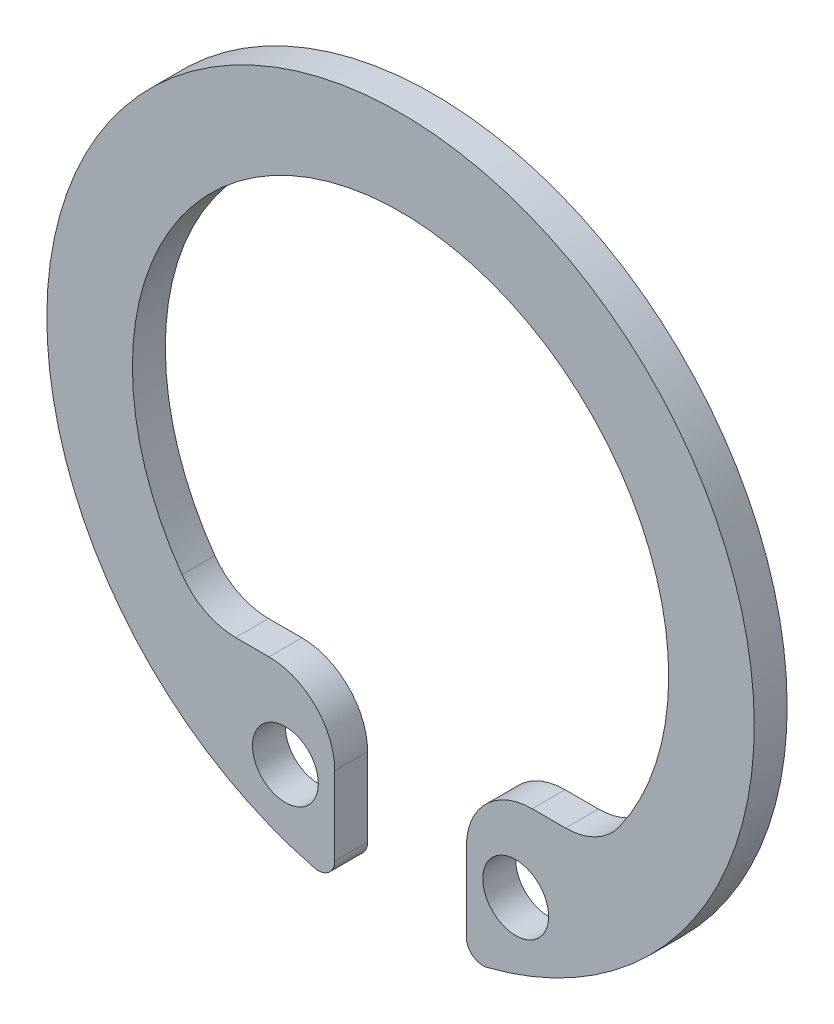
SolidWorks part; units mm, degrees
ref_plane "Ön Düzlem" through (0, 0, 0) normal (0, 0, 1) x (1, 0, 0)
ref_plane "Üst Düzlem" through (0, 0, 0) normal (0, 1, 0) x (1, 0, 0)
ref_plane "Sağ Düzlem" through (0, 0, 0) normal (1, 0, 0) x (0, 0, -1)
sketch "Çizim1" plane through (0, 0, 0) normal (0, 0, 1) x (1, 0, 0)
  line L0 (0, -8.15) -> (0, -10.75) construction
  line L1 (-2, -5.5623) -> (-2, -10.5623)
  line L2 (2, -5.5623) -> (2, -10.5623)
  line L3 (-2, -8.15) -> (-2, -10.75) construction
  line L4 (2, -8.15) -> (2, -10.75) construction
  line L5 (-2, -5.5623) -> (-5.9568, -5.5623)
  line L6 (2, -5.5623) -> (5.9568, -5.5623)
  arc A0 (2, -10.5623) -> (-2, -10.5623) centre (0, 0) ccw
  arc A1 (5.9568, -5.5623) -> (-5.9568, -5.5623) centre (0, 0) ccw
  circle A2 centre (-3.5, -8.15) radius 1
  circle A3 centre (3.5, -8.15) radius 1
  dimension "D1" = 21.5
  dimension "D2" = 16.3
  dimension "D6" = 2
  dimension "D7" = 2
  dimension "D8" = 3.5
  dimension "D9" = 3.5
  dimension "D3" = 2
  dimension "D5" = 5
  dimension "D4" = 2
extrude "Yükseklik-Ekstrüzyon1" add sketch "Çizim1" along normal blind 1
fillet "Radyus1" radius 2 4 edges at (5.9568, -5.5623, 0.5) (-5.9568, -5.5623, 0.5) (2, -5.5623, 0.5) (-2, -5.5623, 0.5)
fillet "Radyus2" radius 0.5 2 edges at (2, -10.5623, 0.5) (-2, -10.5623, 0.5)
